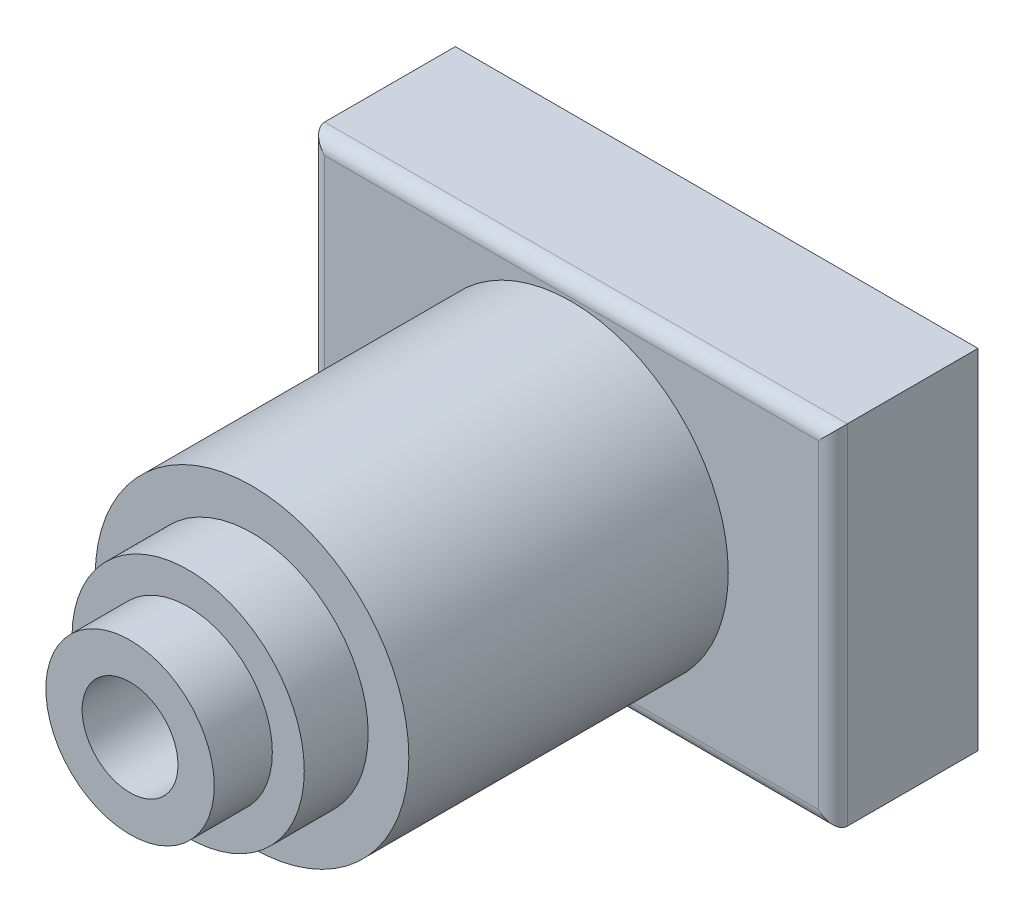
SolidWorks part; units mm, degrees
ref_plane "前视基准面" through (0, 0, 0) normal (0, 0, 1) x (1, 0, 0)
ref_plane "上视基准面" through (0, 0, 0) normal (0, 1, 0) x (1, 0, 0)
ref_plane "右视基准面" through (0, 0, 0) normal (1, 0, 0) x (0, 0, -1)
other "Configuration Table"
sketch "草图1" plane through (0, 0, 0) normal (0, 0, 1) x (1, 0, 0)
  line L1 (-9, 6) -> (9, 6)
  line L2 (-9, 6) -> (-9, -6)
  line L3 (-9, -6) -> (9, -6)
  line L4 (9, 6) -> (9, -6)
  line L5 (-9, 6) -> (9, -6) construction
  line L6 (-9, -6) -> (9, 6) construction
  point P0 (0, 0)
extrude "凸台-拉伸1" add sketch "草图1" along normal blind 5
sketch "草图2" plane through (0, 0, 5) normal (0, 0, 1) x (1, 0, 0)
  circle A0 centre (0, 0) radius 5.4
extrude "凸台-拉伸2" add sketch "草图2" along normal blind 11
sketch "草图3" plane through (0, 0, 16) normal (0, 0, 1) x (1, 0, 0)
  circle A0 centre (0, 0) radius 4
extrude "凸台-拉伸3" add sketch "草图3" along normal blind 2.2 contours A0
sketch "草图4" plane through (0, 0, 18.2) normal (0, 0, 1) x (1, 0, 0)
  circle A0 centre (0, 0) radius 2.9
extrude "凸台-拉伸4" add sketch "草图4" along normal blind 2
sketch "草图5" plane through (0, 0, 20.2) normal (0, 0, 1) x (1, 0, 0)
  circle A0 centre (0, 0) radius 1.65
extrude "切除-拉伸1" cut sketch "草图5" against normal blind 25
sketch "草图6" plane through (0, 0, 0) normal (0, 0, -1) x (-1, 0, 0)
  circle A0 centre (0, 0) radius 4.5
extrude "切除-拉伸2" cut sketch "草图6" against normal blind 2
fillet "圆角1" radius 0.5 4 edges at (-9, 0, 5) (0, -6, 5) (9, 0, 5) (0, 6, 5)
